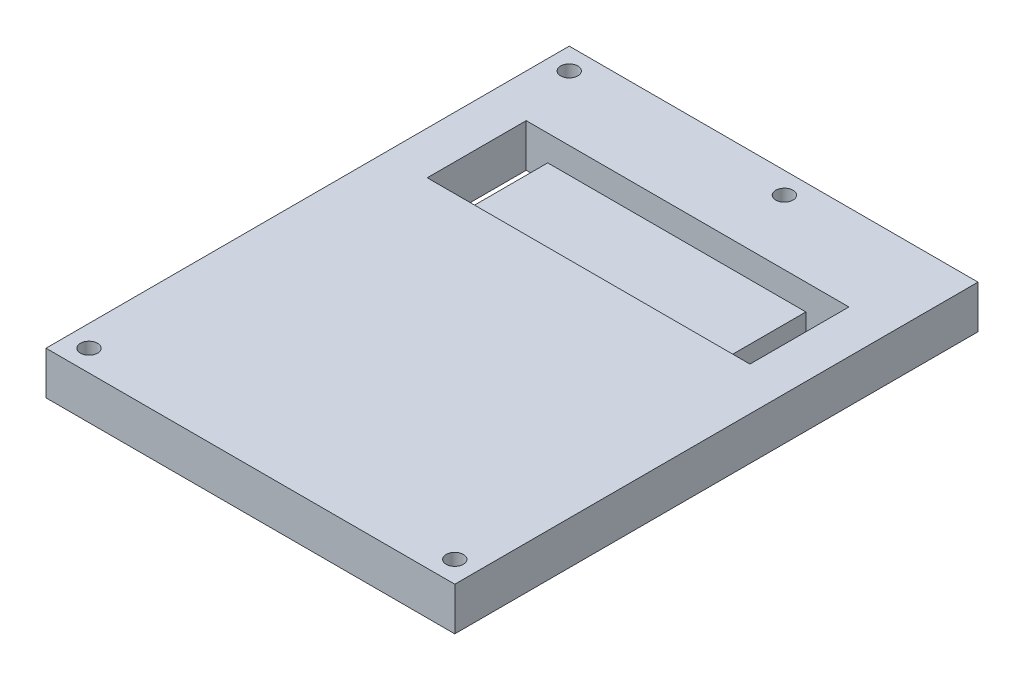
SolidWorks part; units mm, degrees
ref_plane "前视基准面" through (0, 0, 0) normal (0, 0, 1) x (1, 0, 0)
ref_plane "上视基准面" through (0, 0, 0) normal (0, 1, 0) x (1, 0, 0)
ref_plane "右视基准面" through (0, 0, 0) normal (1, 0, 0) x (0, 0, -1)
other "Configuration Table"
sketch "草图1" plane through (0, 0, 0) normal (0, 1, 0) x (1, 0, 0)
  line L1 (-54.4053, 33.3382) -> (-6.9053, 33.3382)
  line L2 (-54.4053, 33.3382) -> (-54.4053, -27.4618)
  line L3 (-54.4053, -27.4618) -> (-6.9053, -27.4618)
  line L4 (-6.9053, 33.3382) -> (-6.9053, -27.4618)
  line L5 (-54.4053, 33.3382) -> (-49.4053, 33.3382) construction
  line L6 (-54.4053, 33.3382) -> (-54.4053, 23.3382) construction
  point P4 (0, 0)
  point P7 (0, 0)
  point P8 (0, 0)
  point P9 (0, 0)
  dimension "D1" = 47.5
  dimension "D2" = 60.8
extrude "凸台-拉伸1" add sketch "草图1" against normal blind 5 contours L4 L3 L2 L1
sketch "草图2" plane through (0, 0, 0) normal (0, 1, 0) x (1, 0, 0)
  line L0 (-54.4053, 33.3382) -> (-54.4053, -27.4618) construction
  line L1 (-49.4053, 23.3382) -> (-11.9053, 23.3382)
  line L2 (-49.4053, 23.3382) -> (-49.4053, 11.8382)
  line L3 (-49.4053, 11.8382) -> (-11.9053, 11.8382)
  line L4 (-11.9053, 23.3382) -> (-11.9053, 11.8382)
  line L5 (-54.4053, 33.3382) -> (-6.9053, 33.3382) construction
  dimension "D1" = 5
  dimension "D2" = 10
  dimension "D3" = 11.5
  dimension "D4" = 37.5
extrude "切除-拉伸1" cut sketch "草图2" against normal blind 3 contours L2 L3 L4 L1
sketch "草图3" plane through (0, -3, 0) normal (0, 1, 0) x (1, 0, 0)
  line L0 (-49.4053, 11.8382) -> (-11.9053, 11.8382) construction
  line L3 (-49.4053, 23.3382) -> (-46.9053, 23.3382)
  line L4 (-49.4053, 23.3382) -> (-49.4053, 11.8382)
  line L5 (-49.4053, 11.8382) -> (-46.9053, 11.8382)
  line L6 (-46.9053, 23.3382) -> (-46.9053, 11.8382)
  line L7 (-49.4053, 11.8382) -> (-11.9053, 11.8382) construction
  line L8 (-11.9053, 23.3382) -> (-16.9053, 23.3382)
  line L9 (-11.9053, 23.3382) -> (-11.9053, 11.8382)
  line L10 (-11.9053, 11.8382) -> (-16.9053, 11.8382)
  line L11 (-16.9053, 23.3382) -> (-16.9053, 11.8382)
  dimension "D1" = 2.5
  dimension "D2" = 5
extrude "切除-拉伸2" cut sketch "草图3" against normal blind 2
sketch "草图4" plane through (0, 0, 0) normal (0, 1, 0) x (1, 0, 0)
  line L0 (-6.9053, 33.3382) -> (-6.9053, -27.4618) construction
  line L3 (-54.4053, -27.4618) -> (-6.9053, -27.4618) construction
  line L4 (-54.4053, 33.3382) -> (-54.4053, -27.4618) construction
  line L5 (-54.4053, 33.3382) -> (-6.9053, 33.3382) construction
  circle A0 centre (-9.4053, -24.9618) radius 1
  circle A1 centre (-51.9053, -24.9618) radius 1
  circle A2 centre (-51.9053, 30.8382) radius 1
  circle A3 centre (-26.9053, 30.8382) radius 1
  dimension "D1" = 2.5
  dimension "D3" = 2.5
  dimension "D5" = 2.5
  dimension "D7" = 20
  dimension "D2" = 2.5
  dimension "D4" = 2.5
  dimension "D6" = 2.5
  dimension "D8" = 2.5
extrude "切除-拉伸3" cut sketch "草图4" against normal blind 5
